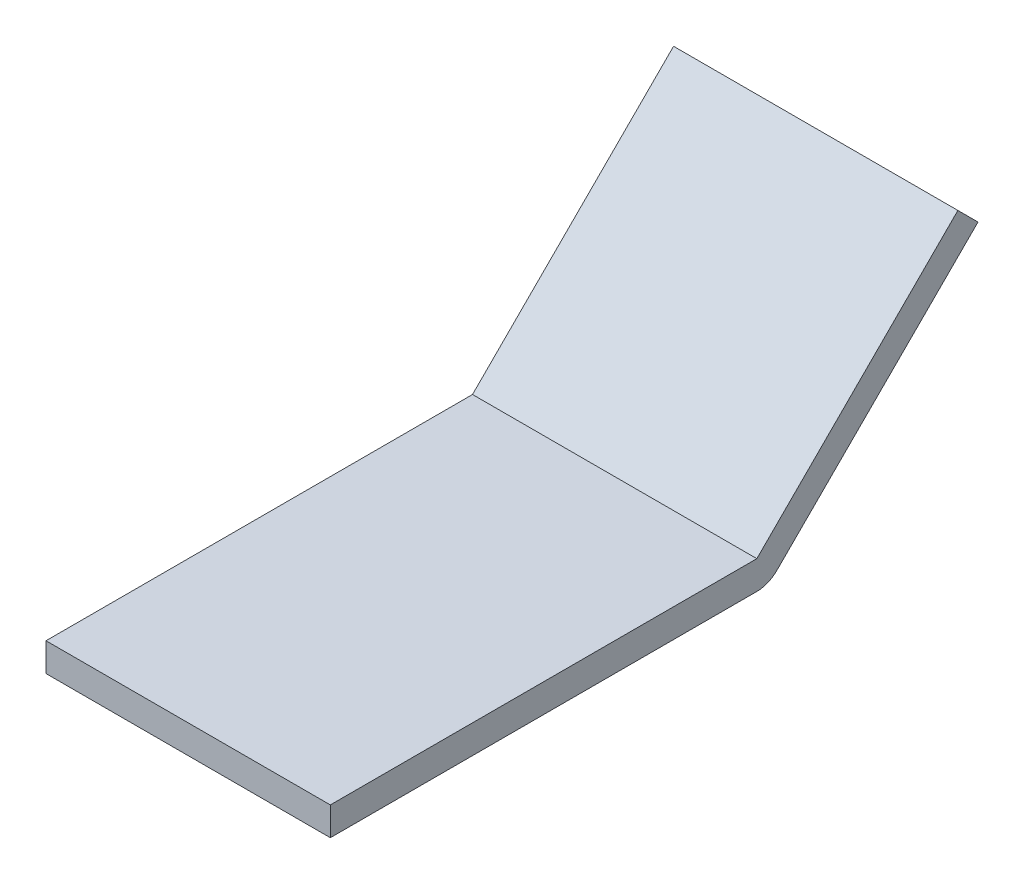
SolidWorks part; units mm, degrees
ref_plane "Front Plane" through (0, 0, 0) normal (0, 0, 1) x (1, 0, 0)
ref_plane "Top Plane" through (0, 0, 0) normal (0, 1, 0) x (1, 0, 0)
ref_plane "Right Plane" through (0, 0, 0) normal (1, 0, 0) x (0, 0, -1)
sketch "Sketch1" plane through (0, 0, 0) normal (1, 0, 0) x (0, 0, -1)
  line L0 (0, 0) -> (180, 0)
  line L1 (180, 0) -> (264.8528, 84.8528)
  line L2 (188.4853, -8.4853) -> (273.3381, 76.3675)
  line L3 (0, -12) -> (180, -12)
  line L4 (0, 0) -> (0, -12)
  line L5 (264.8528, 84.8528) -> (273.3381, 76.3675)
  arc A0 (180, -12) -> (188.4853, -8.4853) centre (180, 0) ccw
  dimension "D5" = 12
  dimension "Length" = 180
  dimension "D2" = 135
  dimension "D3" = 120
  dimension "D4" = 12
extrude "Extrude1" add sketch "Sketch1" along normal blind 120
